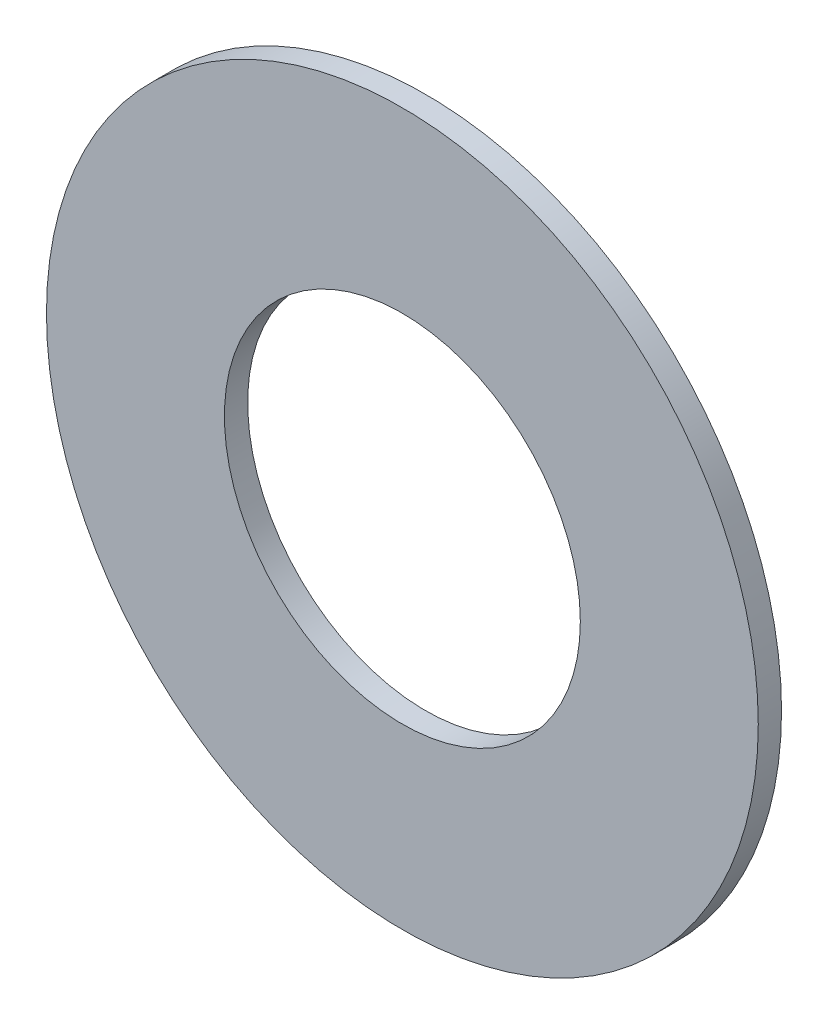
SolidWorks part; units mm, degrees
ref_plane "Front Plane" through (0, 0, 0) normal (0, 0, 1) x (1, 0, 0)
ref_plane "Top Plane" through (0, 0, 0) normal (0, 1, 0) x (1, 0, 0)
ref_plane "Right Plane" through (0, 0, 0) normal (1, 0, 0) x (0, 0, -1)
sketch "Sketch2" plane through (0, 0, 0) normal (0, 0, 1) x (1, 0, 0)
  circle A0 centre (0, 0) radius 19.05
  circle A1 centre (0, 0) radius 9.525
  dimension "D1" = 38.1
  dimension "D2" = 19.05
extrude "Boss-Extrude1" add sketch "Sketch2" along normal blind 1.2446
